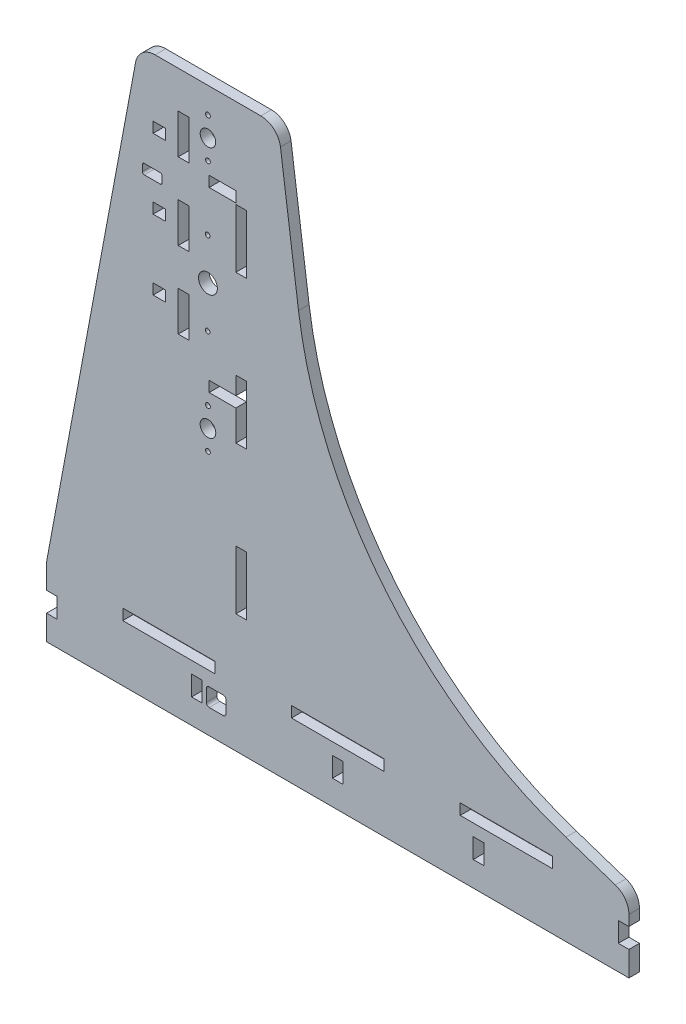
SolidWorks part; units mm, degrees
ref_plane "Front Plane" through (0, 0, 0) normal (0, 0, 1) x (1, 0, 0)
ref_plane "Top Plane" through (0, 0, 0) normal (0, 1, 0) x (1, 0, 0)
ref_plane "Right Plane" through (0, 0, 0) normal (1, 0, 0) x (0, 0, -1)
sketch "Model" plane through (0, 0, 0) normal (0, 0, 1) x (1, 0, 0)
  line L0 (44.9761, 275.8346) -> (0.1697, 35.7434)
  line L1 (108.1936, 284) -> (54.8064, 284)
  line L2 (127.2117, 208.394) -> (118.1023, 275.3481)
  line L3 (287.1623, 37.2792) -> (262.1404, 45.6199)
  line L4 (294, 27.7924) -> (294, 22.5)
  line L5 (294, 22.5) -> (288.65, 22.5)
  line L6 (288.65, 22.5) -> (288.65, 12.5)
  line L7 (288.65, 12.5) -> (294, 12.5)
  line L8 (294, 12.5) -> (294, 0)
  line L9 (294, 0) -> (0, 0)
  line L10 (0, 12.5) -> (0, 0)
  line L11 (5.35, 12.5) -> (0, 12.5)
  line L12 (5.35, 22.5) -> (5.35, 12.5)
  line L13 (0, 22.5) -> (5.35, 22.5)
  line L14 (0, 33.9088) -> (0, 22.5)
  line L15 (255.5, 34) -> (255.5, 28.5)
  line L16 (208.8333, 34) -> (255.5, 34)
  line L17 (208.8333, 28.5) -> (208.8333, 34)
  line L18 (255.5, 28.5) -> (208.8333, 28.5)
  line L19 (170.3333, 34) -> (170.3333, 28.5)
  line L20 (123.6667, 34) -> (170.3333, 34)
  line L21 (123.6667, 28.5) -> (123.6667, 34)
  line L22 (170.3333, 28.5) -> (123.6667, 28.5)
  line L23 (85.1667, 34) -> (85.1667, 28.5)
  line L24 (38.5, 34) -> (85.1667, 34)
  line L25 (38.5, 28.5) -> (38.5, 34)
  line L26 (85.1667, 28.5) -> (38.5, 28.5)
  line L27 (215.4037, 22.5) -> (220.7537, 22.5)
  line L28 (215.4037, 12.5) -> (215.4037, 22.5)
  line L29 (220.7537, 12.5) -> (215.4037, 12.5)
  line L30 (220.7537, 22.5) -> (220.7537, 12.5)
  line L31 (144.325, 22.5) -> (149.675, 22.5)
  line L32 (144.325, 12.5) -> (144.325, 22.5)
  line L33 (149.675, 12.5) -> (144.325, 12.5)
  line L34 (149.675, 22.5) -> (149.675, 12.5)
  line L35 (73.2463, 22.5) -> (78.5963, 22.5)
  line L36 (73.2463, 12.5) -> (73.2463, 22.5)
  line L37 (78.5963, 12.5) -> (73.2463, 12.5)
  line L38 (78.5963, 22.5) -> (78.5963, 12.5)
  line L39 (71.85, 167.75) -> (66.5, 167.75)
  line L40 (71.85, 187.75) -> (71.85, 167.75)
  line L41 (66.5, 187.75) -> (71.85, 187.75)
  line L42 (66.5, 167.75) -> (66.5, 187.75)
  line L43 (60.15, 183.825) -> (60.15, 178.475)
  line L44 (53.8, 183.825) -> (60.15, 183.825)
  line L45 (53.8, 178.475) -> (53.8, 183.825)
  line L46 (60.15, 178.475) -> (53.8, 178.475)
  line L47 (60.15, 219.175) -> (60.15, 213.825)
  line L48 (53.8, 219.175) -> (60.15, 219.175)
  line L49 (53.8, 213.825) -> (53.8, 219.175)
  line L50 (60.15, 213.825) -> (53.8, 213.825)
  line L51 (71.85, 206.5) -> (66.5, 206.5)
  line L52 (71.85, 226.5) -> (71.85, 206.5)
  line L53 (66.5, 226.5) -> (71.85, 226.5)
  line L54 (66.5, 206.5) -> (66.5, 226.5)
  line L55 (60.15, 254.525) -> (60.15, 249.175)
  line L56 (53.8, 254.525) -> (60.15, 254.525)
  line L57 (53.8, 249.175) -> (53.8, 254.525)
  line L58 (60.15, 249.175) -> (53.8, 249.175)
  line L59 (71.85, 245.25) -> (66.5, 245.25)
  line L60 (71.85, 265.25) -> (71.85, 245.25)
  line L61 (66.5, 265.25) -> (71.85, 265.25)
  line L62 (66.5, 245.25) -> (66.5, 265.25)
  line L63 (82.1, 239.65) -> (82.1, 245)
  line L64 (95.6, 239.65) -> (82.1, 239.65)
  line L65 (95.6, 245) -> (95.6, 239.65)
  line L66 (82.1, 245) -> (95.6, 245)
  line L67 (95.6, 89.6667) -> (100.95, 89.6667)
  line L68 (95.6, 60) -> (95.6, 89.6667)
  line L69 (100.95, 60) -> (95.6, 60)
  line L70 (100.95, 89.6667) -> (100.95, 60)
  line L71 (95.6, 209.3333) -> (95.6, 239)
  line L72 (100.95, 209.3333) -> (95.6, 209.3333)
  line L73 (100.95, 239) -> (100.95, 209.3333)
  line L74 (95.6, 239) -> (100.95, 239)
  line L75 (95.6, 164.3333) -> (100.95, 164.3333)
  line L76 (82.1, 155.35) -> (95.6, 155.35)
  line L77 (82.1, 150) -> (82.1, 155.35)
  line L78 (95.6, 150) -> (82.1, 150)
  line L79 (95.6, 134.6667) -> (95.6, 150)
  line L80 (100.95, 134.6667) -> (95.6, 134.6667)
  line L81 (100.95, 164.3333) -> (100.95, 134.6667)
  line L82 (58.4052, 229.8007) -> (58.4052, 232.8007)
  line L83 (57.4052, 233.8007) -> (49.4052, 233.8007)
  line L84 (48.4052, 232.8007) -> (48.4052, 229.8007)
  line L85 (49.4052, 228.8007) -> (57.4052, 228.8007)
  line L86 (90.6464, 13.8312) -> (90.6464, 19.8312)
  line L87 (89.1464, 21.3312) -> (82.1464, 21.3312)
  line L88 (80.6464, 19.8312) -> (80.6464, 13.8312)
  line L89 (82.1464, 12.3312) -> (89.1464, 12.3312)
  line L90 (95.6, 155.35) -> (95.6, 164.3333)
  circle A0 centre (81.5, 261) radius 3.915
  circle A1 centre (81.5, 134) radius 3.95
  arc A2 (54.8064, 284) -> (44.9761, 275.8346) centre (54.8064, 274) ccw
  arc A3 (118.1023, 275.3481) -> (108.1936, 284) centre (108.1936, 274) ccw
  arc A4 (127.2117, 208.394) -> (262.1404, 45.6199) centre (325.3859, 235.3565) ccw
  arc A5 (294, 27.7924) -> (287.1623, 37.2792) centre (284, 27.7924) ccw
  arc A6 (0.1697, 35.7434) -> (0, 33.9088) centre (10, 33.9088) ccw
  circle A7 centre (81.5, 197.5) radius 4.75
  circle A8 centre (81.5, 144) radius 1.2
  circle A9 centre (81.5, 124) radius 1.2
  circle A10 centre (81.5, 271) radius 1.2
  circle A11 centre (81.5, 251) radius 1.2
  circle A12 centre (81.34, 218.5) radius 1.2
  circle A13 centre (81.34, 176.5) radius 1.2
  arc A14 (57.4052, 228.8007) -> (58.4052, 229.8007) centre (57.4052, 229.8007) ccw
  arc A15 (58.4052, 232.8007) -> (57.4052, 233.8007) centre (57.4052, 232.8007) ccw
  arc A16 (49.4052, 233.8007) -> (48.4052, 232.8007) centre (49.4052, 232.8007) ccw
  arc A17 (48.4052, 229.8007) -> (49.4052, 228.8007) centre (49.4052, 229.8007) ccw
  arc A18 (89.1464, 12.3312) -> (90.6464, 13.8312) centre (89.1464, 13.8312) ccw
  arc A19 (90.6464, 19.8312) -> (89.1464, 21.3312) centre (89.1464, 19.8312) ccw
  arc A20 (82.1464, 21.3312) -> (80.6464, 19.8312) centre (82.1464, 19.8312) ccw
  arc A21 (80.6464, 13.8312) -> (82.1464, 12.3312) centre (82.1464, 13.8312) ccw
  dimension "D6" = 10
  dimension "D8" = 200
  dimension "D10" = 10
  dimension "D12" = 10
  dimension "D42" = 1.5
  dimension "D46" = 1.5
  dimension "D47" = 1.5
  dimension "D48" = 1.5
  dimension "D55" = 7.9
  dimension "D57" = 2.4
  dimension "D58" = 5.35
  dimension "D61" = 15.3333
  dimension "D56" = 2.4
  dimension "D64" = 2.4
  dimension "D69" = 9.5
  dimension "D74" = 2.4
  dimension "D81" = 1
  dimension "D82" = 1
  dimension "D83" = 1
  dimension "D84" = 1
  dimension "D85" = 2.4
  dimension "D86" = 7.83
  dimension "D91" = 2.4
  dimension "D92" = 13
  dimension "D101" = 65.5
  dimension "D102" = 86.5
  dimension "D106" = 150
  dimension "D107" = 107.5
  dimension "D1" = 294
  dimension "D2" = 12.5
  dimension "D3" = 5.35
  dimension "D4" = 10
  dimension "D5" = 5.2924
  dimension "D7" = 26.3754
  dimension "D9" = 67.5709
  dimension "D11" = 53.3872
  dimension "D13" = 244.2364
  dimension "D14" = 11.4088
  dimension "D15" = 12.5
  dimension "D16" = 10
  dimension "D17" = 5.35
  dimension "D18" = 46.6667
  dimension "D19" = 5.5
  dimension "D20" = 10
  dimension "D21" = 5.35
  dimension "D22" = 38.5
  dimension "D23" = 73.2463
  dimension "D24" = 12.5
  dimension "D25" = 28.5
  dimension "D26" = 5.5
  dimension "D27" = 46.6667
  dimension "D28" = 12.5
  dimension "D29" = 28.5
  dimension "D30" = 123.6667
  dimension "D31" = 144.325
  dimension "D32" = 5.35
  dimension "D33" = 10
  dimension "D34" = 29.6667
  dimension "D35" = 5.35
  dimension "D36" = 95.6
  dimension "D37" = 60
  dimension "D38" = 5.5
  dimension "D39" = 46.6667
  dimension "D40" = 28.5
  dimension "D41" = 38.5
  dimension "D43" = 6
  dimension "D44" = 7
  dimension "D45" = 6
  dimension "D49" = 10
  dimension "D50" = 5.35
  dimension "D51" = 12.5
  dimension "D52" = 12.3312
  dimension "D53" = 80.6464
  dimension "D54" = 73.2463
  dimension "D59" = 29.6667
  dimension "D60" = 8.9833
  dimension "D62" = 5.35
  dimension "D63" = 13.5
  dimension "D65" = 5.35
  dimension "D66" = 20
  dimension "D67" = 6.35
  dimension "D68" = 5.35
  dimension "D70" = 5.35
  dimension "D71" = 29.6667
  dimension "D72" = 13.5
  dimension "D73" = 5.35
  dimension "D75" = 5.35
  dimension "D76" = 20
  dimension "D77" = 6.35
  dimension "D78" = 5.35
  dimension "D79" = 3
  dimension "D80" = 8
  dimension "D87" = 5.35
  dimension "D88" = 20
  dimension "D89" = 6.35
  dimension "D90" = 5.35
  dimension "D93" = 23
  dimension "D94" = 18.75
  dimension "D95" = 29.475
  dimension "D96" = 39
  dimension "D97" = 45
  dimension "D98" = 50.1993
  dimension "D99" = 57.5
  dimension "D100" = 64.825
  dimension "D103" = 96.25
  dimension "D104" = 100.175
  dimension "D105" = 119.6667
extrude "Boss-Extrude1" add sketch "Model" along normal blind 5.35
